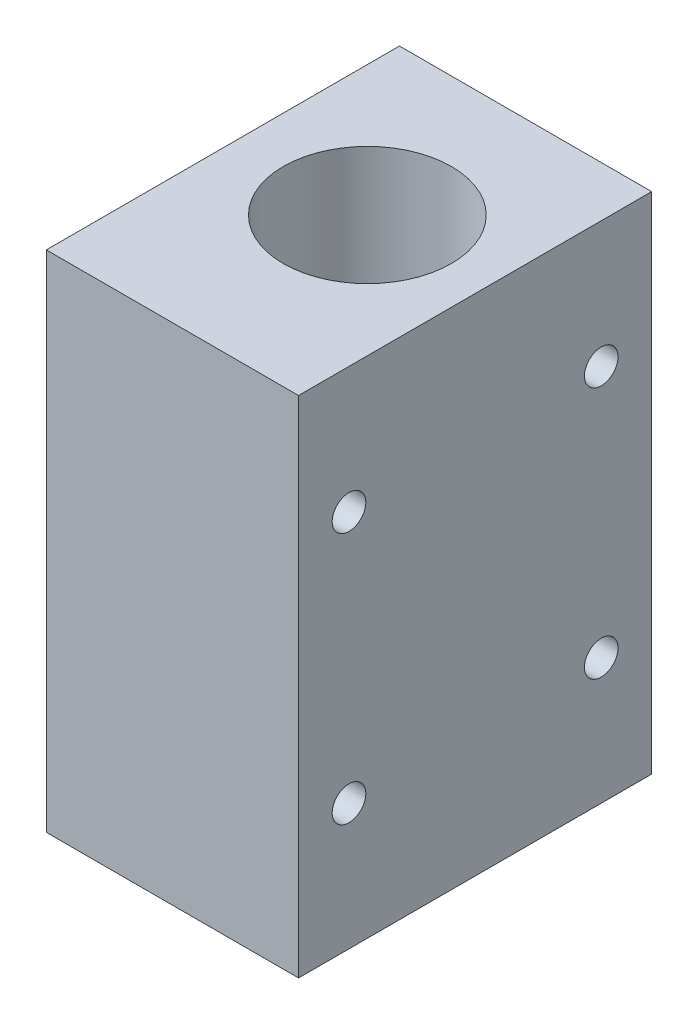
SolidWorks part; units mm, degrees
ref_plane "Front Plane" through (0, 0, 0) normal (0, 0, 1) x (1, 0, 0)
ref_plane "Top Plane" through (0, 0, 0) normal (0, 1, 0) x (1, 0, 0)
ref_plane "Right Plane" through (0, 0, 0) normal (1, 0, 0) x (0, 0, -1)
sketch "Sketch1" plane through (0, 0, 0) normal (1, 0, 0) x (0, 0, -1)
  line L1 (0, 0) -> (42, 0)
  line L2 (0, 0) -> (0, 60)
  line L3 (0, 60) -> (42, 60)
  line L4 (42, 0) -> (42, 60)
  dimension "D1" = 60
  dimension "D2" = 42
extrude "Boss-Extrude1" add sketch "Sketch1" along normal blind 30
sketch "Sketch2" plane through (0, 60, 0) normal (0, 1, 0) x (1, 0, 0)
  line L0 (15.5, 42) -> (15.5, 0) construction
  line L1 (30, 42) -> (0, 42) construction
  line L2 (30, 0) -> (0, 0) construction
  line L3 (30, 42) -> (30, 0) construction
  circle A0 centre (15.5, 22.6823) radius 10
  dimension "D1" = 20
  dimension "D2" = 14.5
extrude "Cut-Extrude1" cut sketch "Sketch2" against normal through all
sketch "Sketch3" plane through (30, 0, 0) normal (1, 0, 0) x (0, 0, -1)
  line L0 (21, 60) -> (21, 0) construction
  line L1 (42, 60) -> (0, 60) construction
  line L2 (0, 0) -> (42, 0) construction
  line L4 (6, 15) -> (36, 15) construction
  line L5 (6, 15) -> (6, 45) construction
  line L6 (6, 45) -> (36, 45) construction
  line L7 (36, 15) -> (36, 45) construction
  line L8 (6, 15) -> (36, 45) construction
  line L9 (6, 45) -> (36, 15) construction
  circle A0 centre (6, 45) radius 2
  circle A1 centre (36, 45) radius 2
  circle A2 centre (36, 15) radius 2
  circle A3 centre (6, 15) radius 2
  point P6 (21, 30)
  dimension "D2" = 4
  dimension "D1" = 30
extrude "Cut-Extrude2" cut sketch "Sketch3" against normal blind 10
